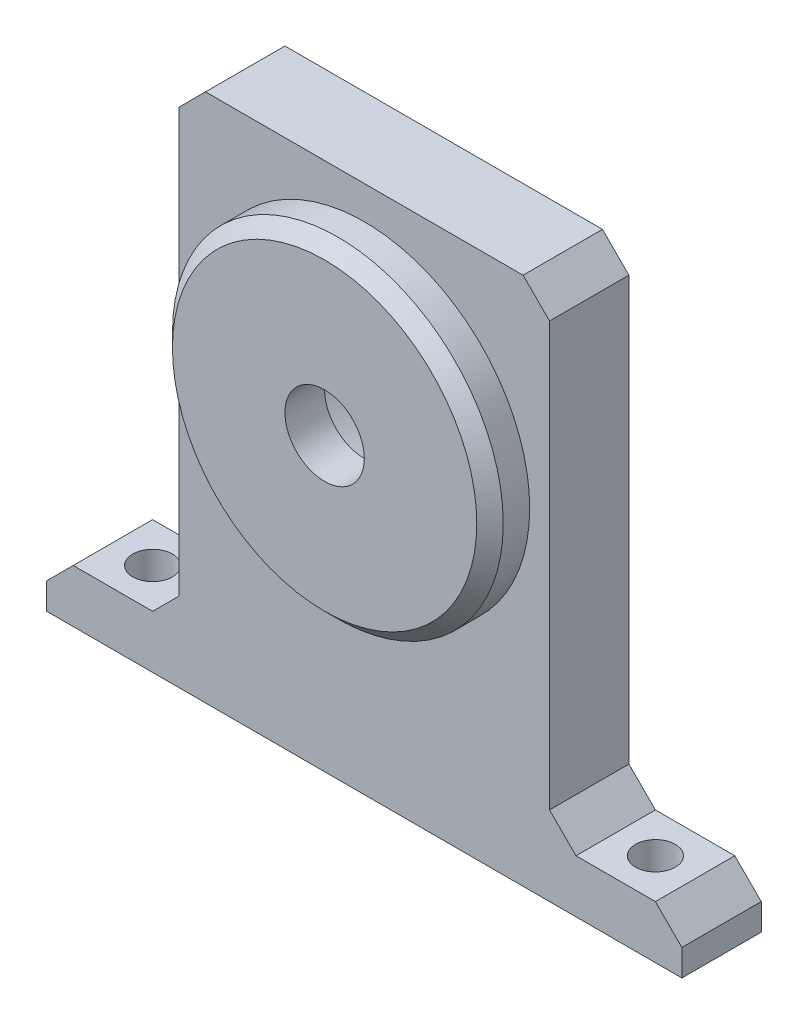
SolidWorks part; units mm, degrees
ref_plane "Front Plane" through (0, 0, 0) normal (0, 0, 1) x (1, 0, 0)
ref_plane "Top Plane" through (0, 0, 0) normal (0, 1, 0) x (1, 0, 0)
ref_plane "Right Plane" through (0, 0, 0) normal (1, 0, 0) x (0, 0, -1)
sketch "Sketch1" plane through (0, 0, 0) normal (0, 0, 1) x (1, 0, 0)
  line L0 (14, 0) -> (14, 40) construction
  line L1 (0, 0) -> (28, 0)
  line L2 (0, 0) -> (0, 40)
  line L3 (0, 40) -> (28, 40)
  line L4 (28, 0) -> (28, 40)
  circle A0 centre (14, 25) radius 9.5
  dimension "D4" = 19
  dimension "D1" = 25
  dimension "D2" = 28
  dimension "D3" = 40
extrude "Boss-Extrude1" add sketch "Sketch1" along normal blind 6
sketch "Sketch2" plane through (0, 0, 0) normal (0, 1, 0) x (1, 0, 0)
  line L1 (0, 0) -> (-10, 0)
  line L2 (0, 0) -> (0, -6)
  line L3 (0, -6) -> (-10, -6)
  line L4 (-10, 0) -> (-10, -6)
  line L5 (28, 0) -> (38, 0)
  line L6 (28, 0) -> (28, -6)
  line L7 (28, -6) -> (38, -6)
  line L8 (38, 0) -> (38, -6)
  dimension "D1" = 10
  dimension "D2" = 6
  dimension "D3" = 10
  dimension "D4" = 6
extrude "Boss-Extrude2" add sketch "Sketch2" along normal blind 4
chamfer "Chamfer1" distance 2 angle 45 6 edges at (28, 4, 3) (38, 4, 3) (-10, 4, 3) (0, 4, 3) (0, 40, 3) (28, 40, 3)
sketch "Sketch3" plane through (0, 4, 0) normal (0, 1, 0) x (1, 0, 0)
  line L0 (-8, -3) -> (36, -3) construction
  line L1 (-8, 0) -> (-8, -6) construction
  line L2 (36, -6) -> (36, 0) construction
  circle A0 centre (-5, -3) radius 1.5
  circle A1 centre (33, -3) radius 1.5
  dimension "D1" = 3
  dimension "D2" = 3
extrude "Cut-Extrude1" cut sketch "Sketch3" against normal through all
sketch "Sketch4" plane through (0, 0, 6) normal (0, 0, 1) x (1, 0, 0)
  circle A0 centre (14, 25) radius 12.5
  circle A1 centre (14, 25) radius 3
  dimension "D1" = 25
  dimension "D2" = 6
extrude "Boss-Extrude3" add sketch "Sketch4" along normal blind 3
chamfer "Chamfer2" distance 1 angle 45 1 edges at (26.5, 25, 9)
